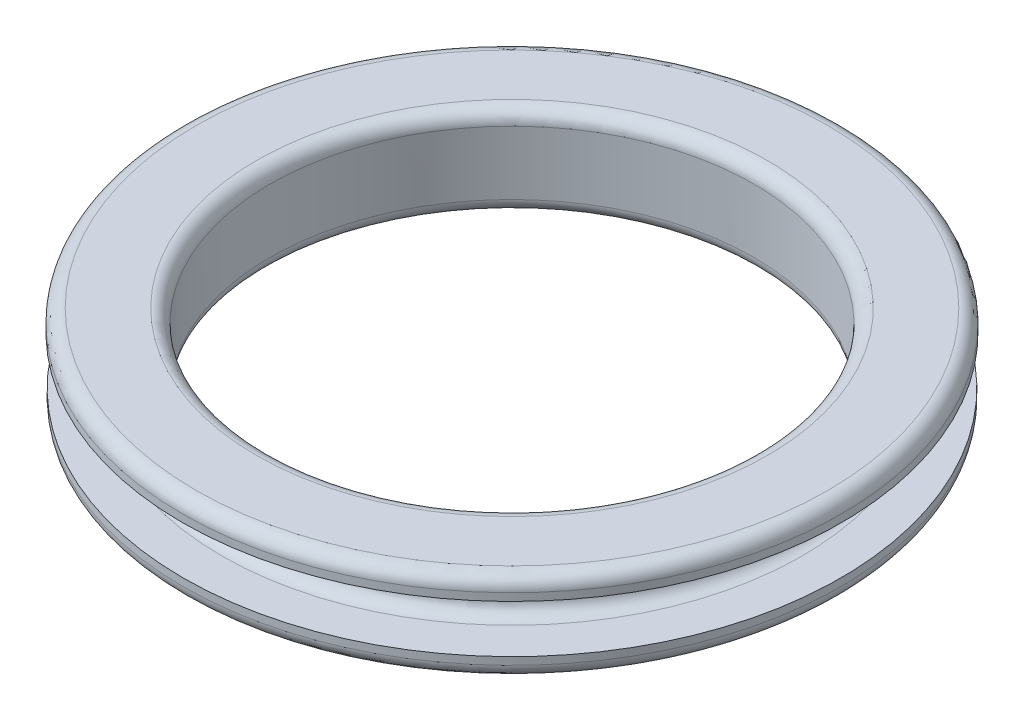
SolidWorks part; units mm, degrees
ref_plane "Front Plane" through (0, 0, 0) normal (0, 0, 1) x (1, 0, 0)
ref_plane "Top Plane" through (0, 0, 0) normal (0, 1, 0) x (1, 0, 0)
ref_plane "Right Plane" through (0, 0, 0) normal (1, 0, 0) x (0, 0, -1)
sketch "Sketch1" plane through (0, 0, 0) normal (0, 0, 1) x (1, 0, 0)
  line L0 (-8, 0) -> (-8, 3)
  line L1 (-8, 3) -> (-10.9, 3)
  line L2 (-10.9, 3) -> (-10.9, 2.3)
  line L3 (-10.9, 2.3) -> (-9.1534, 2.3)
  line L4 (-9.1534, 2.3) -> (-9.1534, 0.7)
  line L5 (-9.1534, 0.7) -> (-10.8718, 0.7)
  line L6 (-10.8718, 0.7) -> (-10.8718, 0)
  line L7 (-10.8718, 0) -> (-8, 0)
  line L8 (0, 7.2469) -> (0, -5.278) construction
  point P11 (-10.9, 2.65)
  dimension "D1" = 8
  dimension "D2" = 3
  dimension "D3" = 0.7
  dimension "D4" = 0.7
  dimension "D5" = 1.6
  dimension "D6" = 2.9
revolve "Revolve1" add sketch "Sketch1" angle 360 about L8
fillet "Fillet1" radius 0.45 6 edges at (0, 3, 10.9) (0, 0, 10.8718) (0, 0, 8) (0, 3, 8) (0, 0.7, 9.1534) (0, 2.3, 9.1534)
